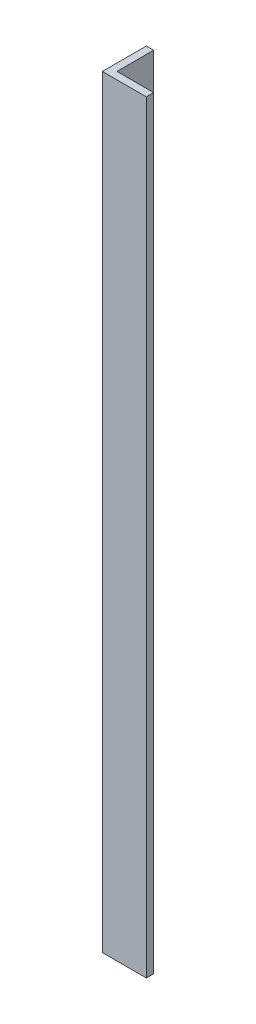
SolidWorks part; units mm, degrees
ref_plane "Front" through (0, 0, 0) normal (0, 0, 1) x (1, 0, 0)
ref_plane "Top" through (0, 0, 0) normal (0, 1, 0) x (1, 0, 0)
ref_plane "Right" through (0, 0, 0) normal (1, 0, 0) x (0, 0, -1)
sketch "Sketch1" plane through (0, 0, 0) normal (0, 1, 0) x (1, 0, 0)
  line L0 (3.175, 3.175) -> (3.175, 19.05)
  line L1 (0, 0) -> (19.05, 0)
  line L2 (0, 0) -> (0, 19.05)
  line L5 (3.175, 3.175) -> (19.05, 3.175)
  line L6 (0, 19.05) -> (3.175, 19.05)
  line L7 (19.05, 0) -> (19.05, 3.175)
  dimension "D1" = 19.05
  dimension "D2" = 3.175
extrude "Boss-Extrude1" add sketch "Sketch1" along normal blind 330.2
sketch "Sketch2" plane through (3.175, 0, 0) normal (1, 0, 0) x (0, 0, -1)
  circle A0 centre (12.7, 53.975) radius 2.413 construction
  circle A1 centre (12.7, 53.975) radius 2.413
  circle A2 centre (12.7, 301.625) radius 2.413 construction
  circle A3 centre (12.7, 301.625) radius 2.413
extrude "Cut-Extrude1" cut sketch "Sketch2" against normal up to next
